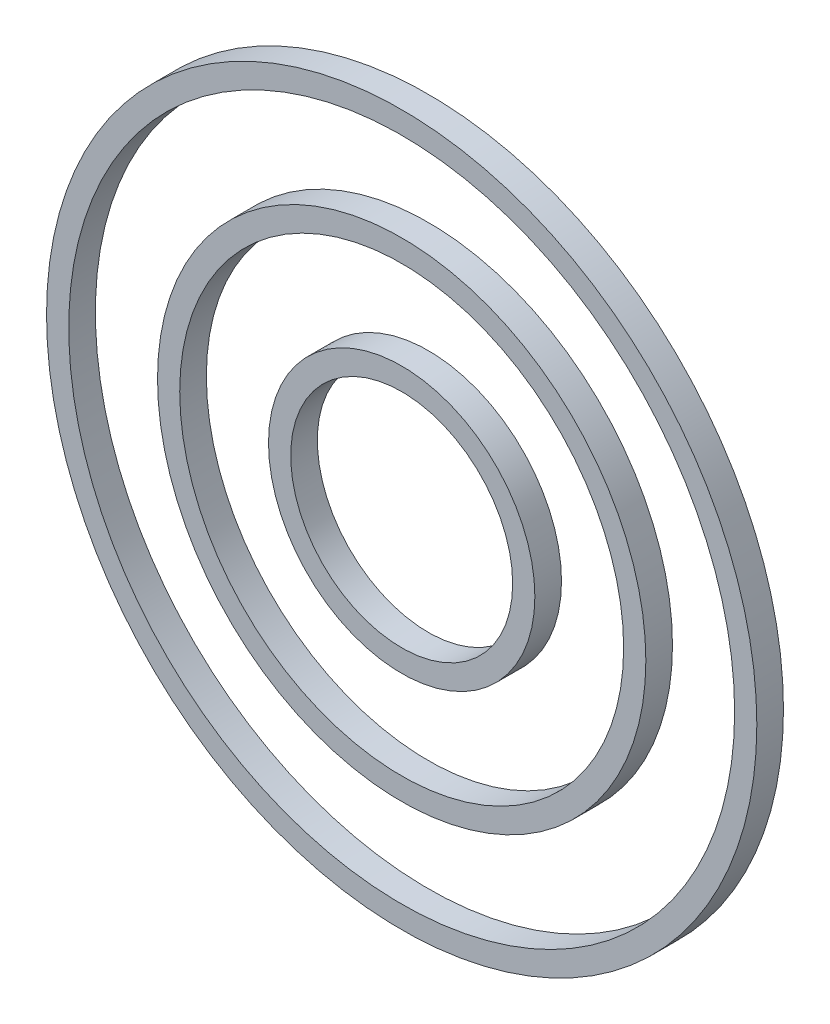
SolidWorks part; units mm, degrees
ref_plane "Front Plane" through (0, 0, 0) normal (0, 0, 1) x (1, 0, 0)
ref_plane "Top Plane" through (0, 0, 0) normal (0, 1, 0) x (1, 0, 0)
ref_plane "Right Plane" through (0, 0, 0) normal (1, 0, 0) x (0, 0, -1)
sketch "Sketch1" plane through (0, 0, 0) normal (0, 0, 1) x (1, 0, 0)
  circle A0 centre (0, 0) radius 25
  circle A1 centre (0, 0) radius 27.5
  circle A2 centre (0, 0) radius 40
  circle A3 centre (0, 0) radius 37.5
  circle A4 centre (0, 0) radius 15
  circle A5 centre (0, 0) radius 12.5
  dimension "D1" = 50
  dimension "D2" = 55
  dimension "D3" = 30
  dimension "D4" = 25
  dimension "D5" = 75
  dimension "D6" = 80
extrude "Boss-Extrude1" add sketch "Sketch1" along normal blind 3 contours A2 A3 | A1 A0 | A4 A5
